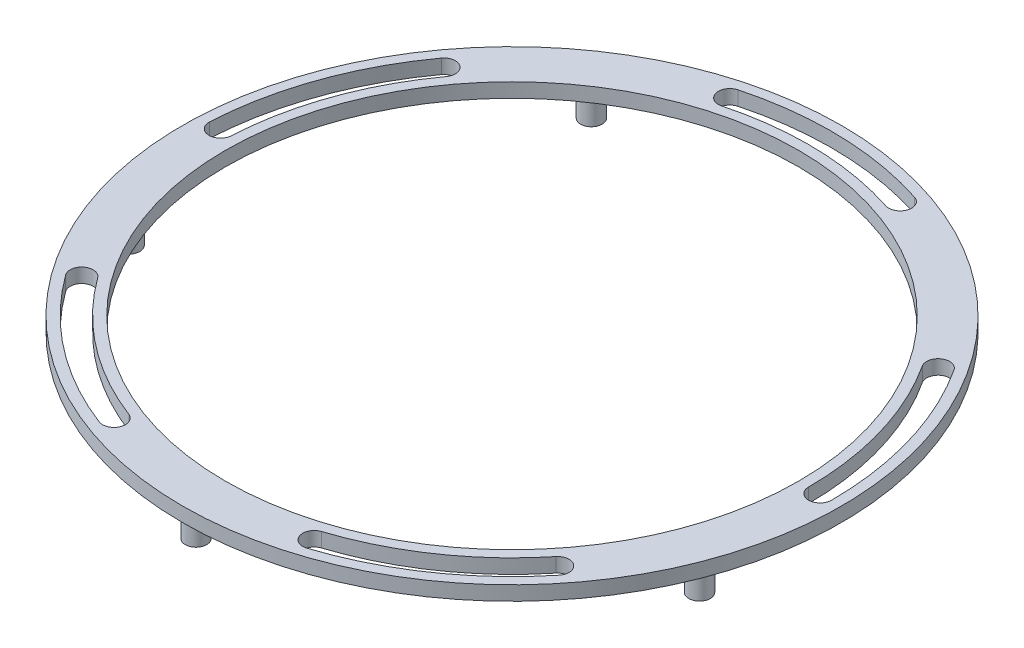
SolidWorks part; units mm, degrees
ref_plane "Front Plane" through (0, 0, 0) normal (0, 0, 1) x (1, 0, 0)
ref_plane "Top Plane" through (0, 0, 0) normal (0, 1, 0) x (1, 0, 0)
ref_plane "Right Plane" through (0, 0, 0) normal (1, 0, 0) x (0, 0, -1)
sketch "Sketch1" plane through (0, 0, 0) normal (0, 1, 0) x (1, 0, 0)
  circle A0 centre (0, 0) radius 46
  circle A1 centre (0, 0) radius 40
  dimension "D1" = 92
  dimension "D2" = 80
extrude "Boss-Extrude1" add sketch "Sketch1" along normal blind 2
sketch "Sketch2" plane through (0, 2, 0) normal (0, 1, 0) x (1, 0, 0)
  line L0 (-51.1462, 0) -> (67.8311, 0) construction
  line L1 (0, 54.0778) -> (0, -57.4459) construction
  line L2 (0, 0) -> (36.0628, 23.4195) construction
  line L3 (0, 0) -> (43, 0) construction
  line L4 (0, 0) -> (26.1767, 34.1142) construction
  arc A0 (36.0628, 23.4195) -> (43, 0) centre (0, 0) cw construction
  arc A1 (44.6, 0) -> (37.4047, 24.2909) centre (0, 0) ccw
  arc A2 (41.4, 0) -> (34.721, 22.5481) centre (0, 0) ccw
  arc A3 (41.4, 0) -> (44.6, 0) centre (43, 0) ccw
  arc A4 (37.4047, 24.2909) -> (34.721, 22.5481) centre (36.0628, 23.4195) ccw
  circle A5 centre (0, 0) radius 43 construction
  circle A6 centre (26.1767, 34.1142) radius 1.5
  point P8 (41.2292, 12.2127)
  dimension "D1" = 43
  dimension "D2" = 1.6
  dimension "D3" = 33
  dimension "D4" = 3
  dimension "D5" = 19.5
extrude "Cut-Extrude1" cut sketch "Sketch2" against normal up to next
sketch "Sketch3" plane through (0, 2, 0) normal (0, 1, 0) x (1, 0, 0)
  circle A0 centre (26.1767, 34.1142) radius 1.5 construction
  circle A1 centre (26.1767, 34.1142) radius 1.5
extrude "Boss-Extrude2" add sketch "Sketch3" against normal blind 6
pattern_circular "CirPattern1" count 5 over 360 about axis through (0, 0, 0) along (0, 1, 0) of "Cut-Extrude1", "Boss-Extrude2"
